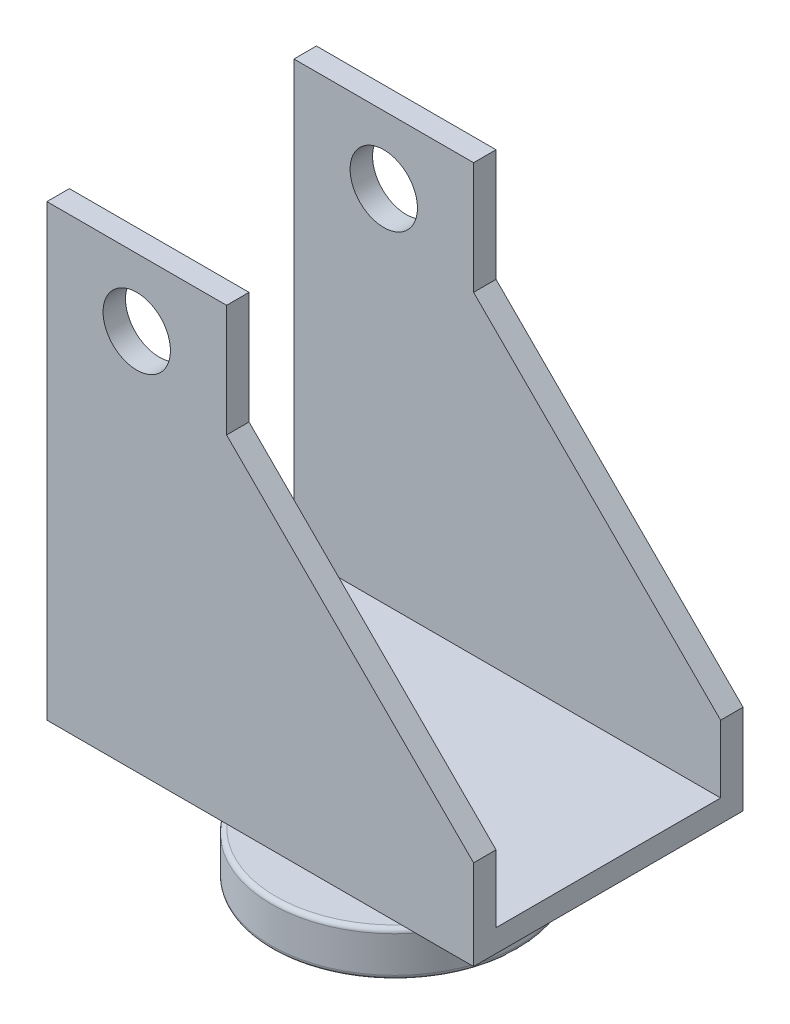
SolidWorks part; units mm, degrees
material "1060 Alloy"
ref_plane "Front Plane" through (0, 0, 0) normal (0, 0, 1) x (1, 0, 0)
ref_plane "Top Plane" through (0, 0, 0) normal (0, 1, 0) x (1, 0, 0)
ref_plane "Right Plane" through (0, 0, 0) normal (1, 0, 0) x (0, 0, -1)
sketch "Sketch1" plane through (0, 0, 0) normal (0, 1, 0) x (1, 0, 0)
  line L0 (0, 0) -> (0, 25)
  line L1 (0, 25) -> (95, 25)
  line L2 (95, 25) -> (95, -25)
  line L3 (95, -25) -> (0, -25)
  line L4 (0, -25) -> (0, 0)
  line L5 (0, 0) -> (95, 0) construction
  dimension "D1" = 95
  dimension "D2" = 50
extrude "Boss-Extrude1" add sketch "Sketch1" along normal blind 5 contours L0 L1 L2 L3 L4
sketch "Sketch2" plane through (0, 0, 25) normal (0, 0, 1) x (1, 0, 0)
  line L0 (0, 0) -> (0, 100)
  line L1 (0, 100) -> (40, 100)
  line L2 (40, 100) -> (40, 75)
  line L3 (40, 75) -> (95, 20)
  line L4 (95, 20) -> (95, 0)
  line L5 (95, 0) -> (0, 0)
  dimension "D1" = 100
  dimension "D2" = 20
  dimension "D3" = 25
  dimension "D4" = 40
extrude "Boss-Extrude2" add sketch "Sketch2" along normal blind 5 contours L5 L0 L1 L2 L3 L4
sketch "Sketch3" plane through (0, 0, 30) normal (0, 0, 1) x (1, 0, 0)
  line L0 (0, 0) -> (0, 100) construction
  line L1 (95, 0) -> (0, 0) construction
  circle A0 centre (20, 85) radius 7.5
  dimension "D3" = 15
  dimension "D1" = 20
  dimension "D2" = 85
extrude "Cut-Extrude1" cut sketch "Sketch3" against normal through all
mirror "Mirror1" about plane through (0, 0, 0) normal (0, 0, 1) of "Cut-Extrude1", "Boss-Extrude2"
sketch "Sketch4" plane through (0, 0, 0) normal (0, -1, 0) x (-1, 0, 0)
  line L0 (0, -30) -> (0, 30) construction
  line L1 (-95, 30) -> (0, 30) construction
  circle A0 centre (-47.5, 0) radius 15
  dimension "D3" = 30
  dimension "D1" = 47.5
  dimension "D2" = 30
extrude "Boss-Extrude3" add sketch "Sketch4" along normal blind 12
sketch "Sketch5" plane through (0, -12, 0) normal (0, -1, 0) x (-1, 0, 0)
  line L0 (0, -30) -> (0, 30) construction
  line L1 (-95, 30) -> (0, 30) construction
  circle A0 centre (-47.5, 0) radius 27.5
  dimension "D3" = 55
  dimension "D1" = 47.5
  dimension "D2" = 30
extrude "Boss-Extrude4" add sketch "Sketch5" along normal blind 10
fillet "Fillet1" radius 1 2 edges at (47.5, -12, -27.5) (47.5, -22, -27.5)
